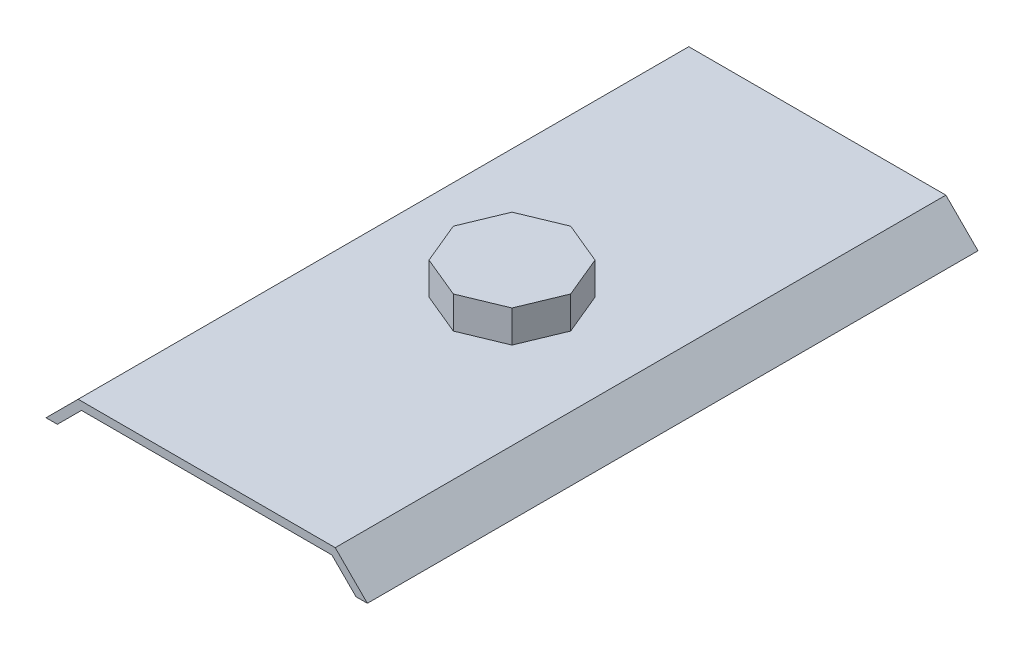
SolidWorks part; units mm, degrees
ref_plane "Front Plane" through (0, 0, 0) normal (0, 0, 1) x (1, 0, 0)
ref_plane "Top Plane" through (0, 0, 0) normal (0, 1, 0) x (1, 0, 0)
ref_plane "Right Plane" through (0, 0, 0) normal (1, 0, 0) x (0, 0, -1)
sketch "Sketch1" plane through (0, 0, 0) normal (0, 0, 1) x (1, 0, 0)
  line L0 (-254, -25.4) -> (-203.2, 25.4)
  line L1 (-203.2, 25.4) -> (203.2, 25.4)
  line L3 (-254, -25.4) -> (254, -25.4)
  line L5 (-207.8182, 20.7818) -> (254, -25.4) construction
  line L6 (-254, -25.4) -> (207.8182, 20.7818) construction
  line L7 (0, 0) -> (0, -78.1831)
  line L8 (254, -25.4) -> (203.2, 25.4)
  line L9 (-197.9395, 12.7) -> (197.9395, 12.7)
  line L10 (223.3395, -12.7) -> (197.9395, 12.7)
  line L11 (-223.3395, -12.7) -> (223.3395, -12.7)
  line L12 (-223.3395, -12.7) -> (-197.9395, 12.7)
  line L13 (-223.3395, -12.7) -> (-236.0395, -25.4)
  line L14 (-236.0395, -25.4) -> (-185.2395, 25.4)
  line L15 (223.3395, -12.7) -> (236.0395, -25.4)
  point P0 (0, 0)
  dimension "D1" = 12.7
extrude "Boss-Extrude4" add sketch "Sketch1" along normal blind 965.2 contours L12 L14 L1 L0 L3 L13 | L10 L15 L3 L8 L1 L14 L9
sketch "Sketch59" plane through (0, 12.7, 0) normal (0, -1, 0) x (-1, 0, 0)
  line L0 (-197.9395, -965.2) -> (-197.9395, 0) construction
  line L1 (-197.9395, -482.6) -> (0, -482.6)
  point P5 (0, -482.6)
sketch "Sketch60" plane through (0, 12.7, 0) normal (0, -1, 0) x (1, 0, 0)
  line L0 (0, 0) -> (197.9395, 0)
  point P5 (0, 0)
move or copy body "Body-Move/Copy1" bodies to move or copy 110 copy no translate (0, 0, -482.6)
sketch "Sketch61" plane through (0, 12.7, 0) normal (0, -1, 0) x (1, 0, 0)
  line L0 (0, 0) -> (0, 254)
  line L1 (0, 0) -> (98.9697, 0)
  line L2 (0, 0) -> (197.9395, 0) construction
  circle A0 centre (145.8082, 254) radius 50.8
  circle A1 centre (145.8082, -254) radius 50.8
  circle A2 centre (-145.8082, -254) radius 50.8
  circle A3 centre (-145.8082, 254) radius 50.8
  circle A4 centre (-145.8082, 254) radius 25.4
  circle A5 centre (145.8082, 254) radius 25.4
  circle A6 centre (-145.8082, -254) radius 25.4
  circle A7 centre (145.8082, -254) radius 25.4
  dimension "D1" = 25.4
extrude "Boss-Extrude5" add sketch "Sketch61" along normal blind 50.8 contours A3 A4 | A0 A5 | A1 A7 | A2 A6
sketch "Sketch62" plane through (0, 25.4, 0) normal (0, 1, 0) x (1, 0, 0)
  line L0 (0, -92.7722) -> (65.5998, -65.5998)
  line L1 (92.7722, 0) -> (65.5998, 65.5998)
  line L2 (65.5998, 65.5998) -> (0, 92.7722)
  line L3 (0, 92.7722) -> (-65.5998, 65.5998)
  line L4 (-65.5998, 65.5998) -> (-92.7722, 0)
  line L5 (-92.7722, 0) -> (-65.5998, -65.5998)
  line L6 (-65.5998, -65.5998) -> (0, -92.7722)
  line L7 (65.5998, -65.5998) -> (92.7722, 0)
  circle A0 centre (0, 0) radius 85.7103 construction
extrude "Boss-Extrude6" add sketch "Sketch62" along normal blind 50.8
